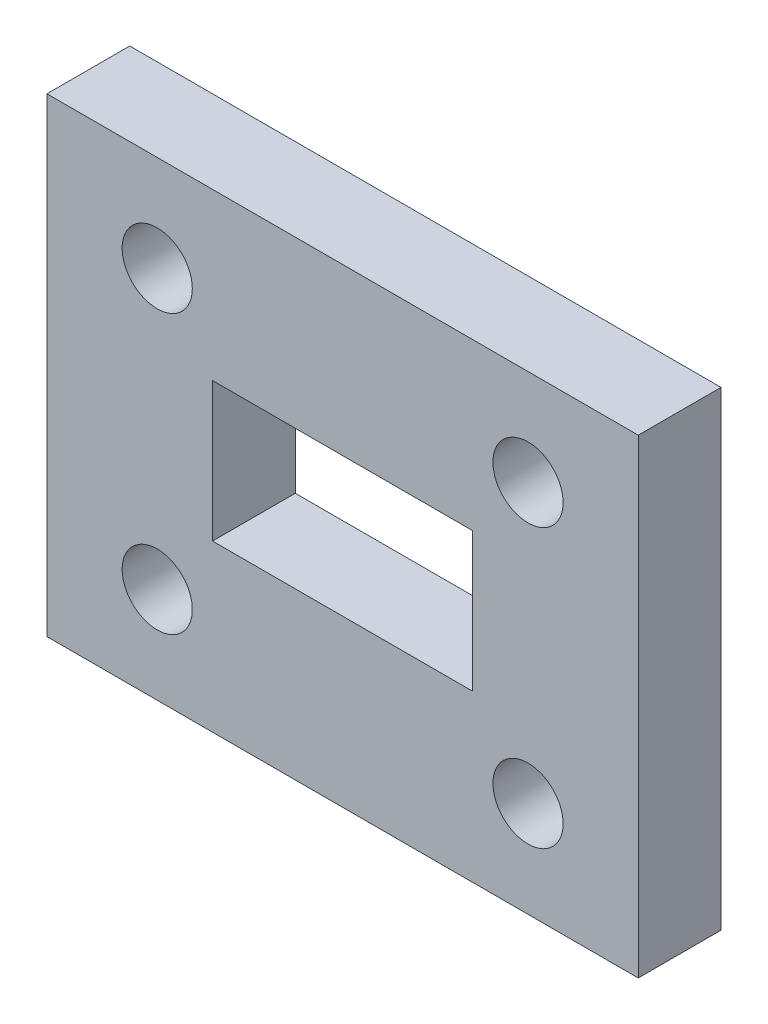
SolidWorks part; units mm, degrees
ref_plane "Front Plane" through (0, 0, 0) normal (0, 0, 1) x (1, 0, 0)
ref_plane "Top Plane" through (0, 0, 0) normal (0, 1, 0) x (1, 0, 0)
ref_plane "Right Plane" through (0, 0, 0) normal (1, 0, 0) x (0, 0, -1)
sketch "Sketch1" plane through (0, 0, 0) normal (0, 0, 1) x (1, 0, 0)
  line L1 (4.9911, -2.667) -> (-4.9911, -2.667) construction
  line L2 (4.9911, -2.667) -> (4.9911, 2.667) construction
  line L3 (4.9911, 2.667) -> (-4.9911, 2.667) construction
  line L4 (-4.9911, -2.667) -> (-4.9911, 2.667) construction
  line L5 (4.9911, -2.667) -> (-4.9911, 2.667) construction
  line L6 (4.9911, 2.667) -> (-4.9911, -2.667) construction
  point P0 (0, 0)
  dimension "D1" = 5.334
  dimension "D2" = 9.9822
sketch "Sketch2" plane through (0, 0, 0) normal (0, 0, 1) x (1, 0, 0)
  line L1 (4.9911, -2.667) -> (-4.9911, -2.667)
  line L2 (4.9911, -2.667) -> (4.9911, 2.667)
  line L3 (4.9911, 2.667) -> (-4.9911, 2.667)
  line L4 (-4.9911, -2.667) -> (-4.9911, 2.667)
  line L5 (4.9911, -2.667) -> (-4.9911, 2.667) construction
  line L6 (4.9911, 2.667) -> (-4.9911, -2.667) construction
  line L7 (4.9911, -2.667) -> (4.9911, 2.667) construction
  line L8 (11.3411, -9.017) -> (-11.3411, -9.017)
  line L9 (11.3411, -9.017) -> (11.3411, 9.017)
  line L10 (11.3411, 9.017) -> (-11.3411, 9.017)
  line L11 (-11.3411, -9.017) -> (-11.3411, 9.017)
  line L12 (11.3411, -9.017) -> (-11.3411, 9.017) construction
  line L13 (11.3411, 9.017) -> (-11.3411, -9.017) construction
  line L14 (4.9911, -2.667) -> (-4.9911, -2.667) construction
  line L15 (0, 9.017) -> (0, -9.017) construction
  line L16 (-11.3411, 0) -> (11.3411, 0) construction
  circle A0 centre (-7.112, 5.334) radius 1.3462
  circle A1 centre (7.112, 5.334) radius 1.3462
  circle A2 centre (7.112, -5.334) radius 1.3462
  circle A3 centre (-7.112, -5.334) radius 1.3462
  point P0 (0, 0)
  dimension "D4" = 2.6924
  dimension "D1" = 6.35
  dimension "D2" = 6.35
  dimension "D3" = 7.112
  dimension "D5" = 5.334
extrude "Boss-Extrude1" add sketch "Sketch2" along normal blind 3.175
